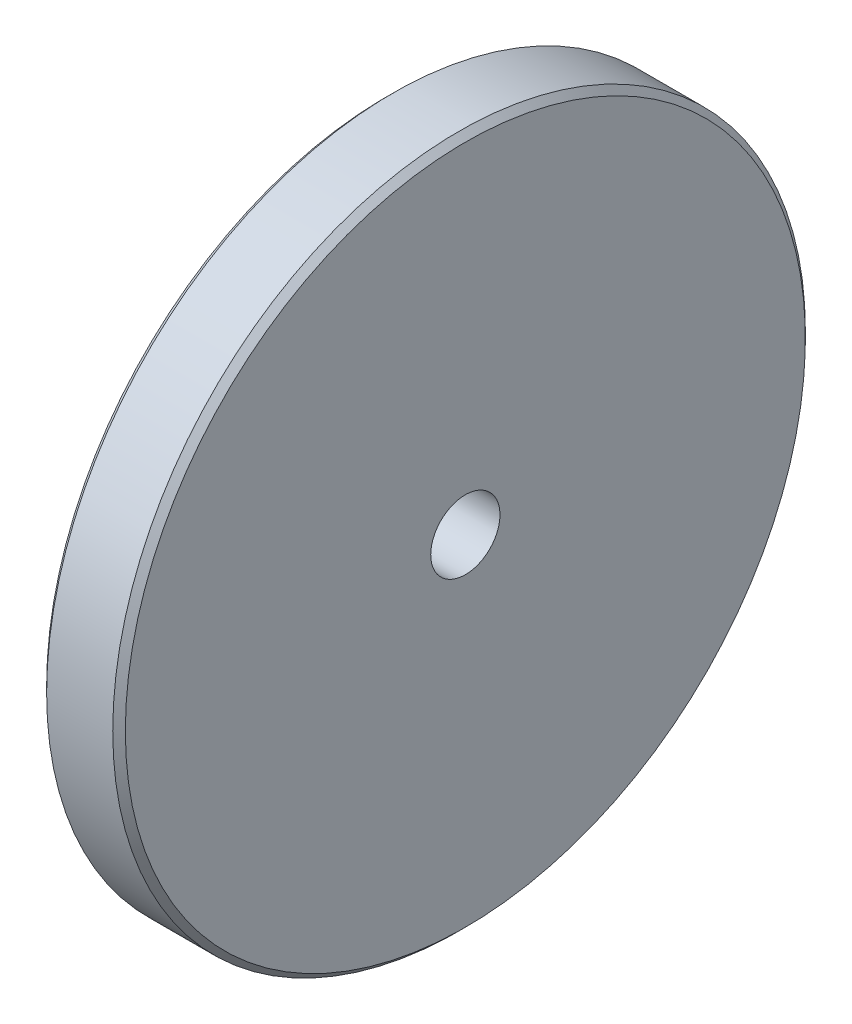
SolidWorks part; units mm, degrees
material "Д16Т ГОСТ 4784-97"
ref_plane "Front Plane" through (0, 0, 0) normal (0, 0, 1) x (1, 0, 0)
ref_plane "Top Plane" through (0, 0, 0) normal (0, 1, 0) x (1, 0, 0)
ref_plane "Right Plane" through (0, 0, 0) normal (1, 0, 0) x (0, 0, -1)
sketch "Skizze1" plane through (0, 0, 0) normal (0, 1, 0) x (1, 0, 0)
  line L0 (0, 0) -> (0, 11)
  line L1 (0, 11) -> (25, 11)
  line L2 (25, 11) -> (25, 0)
  line L3 (0, 0) -> (25, 0)
  line L4 (0, 0) -> (0, 108)
  line L5 (2, 110) -> (23, 110)
  line L6 (25, 108) -> (25, 0)
  line L7 (0, 108) -> (2, 110)
  line L8 (23, 110) -> (25, 108)
  point P7 (0, 110)
  point P8 (25, 110)
revolve "Rotation1" add sketch "Skizze1" angle 360 about L3
